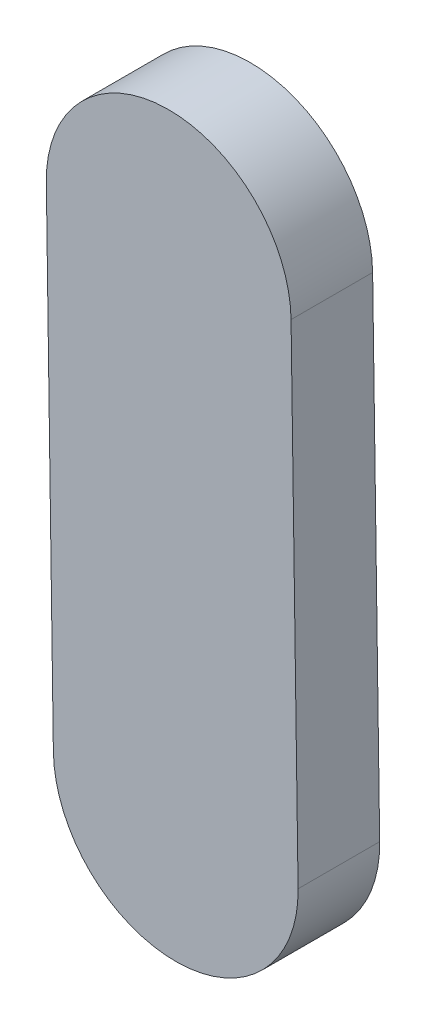
SolidWorks part; units mm, degrees
ref_plane "前视基准面" through (0, 0, 0) normal (0, 0, 1) x (1, 0, 0)
ref_plane "上视基准面" through (0, 0, 0) normal (0, 1, 0) x (1, 0, 0)
ref_plane "右视基准面" through (0, 0, 0) normal (1, 0, 0) x (0, 0, -1)
other "Configuration Table"
sketch "草图1" plane through (0, 0, 0) normal (0, 0, 1) x (1, 0, 0)
  line L0 (-3.8772, 6.2169) -> (-3.7911, 0.2169) construction
  line L1 (-2.3772, 6.2385) -> (-2.2911, 0.2385)
  line L2 (-5.3772, 6.1954) -> (-5.2911, 0.1954)
  arc A0 (-2.3772, 6.2385) -> (-5.3772, 6.1954) centre (-3.8772, 6.2169) ccw
  arc A1 (-5.2911, 0.1954) -> (-2.2911, 0.2385) centre (-3.7911, 0.2169) ccw
  point P2 (-3.8342, 3.2169)
  point P9 (-0.3947, 6.1745)
  dimension "D1" = 6
  dimension "D2" = 3
extrude "凸台-拉伸1" add sketch "草图1" along normal blind 1
